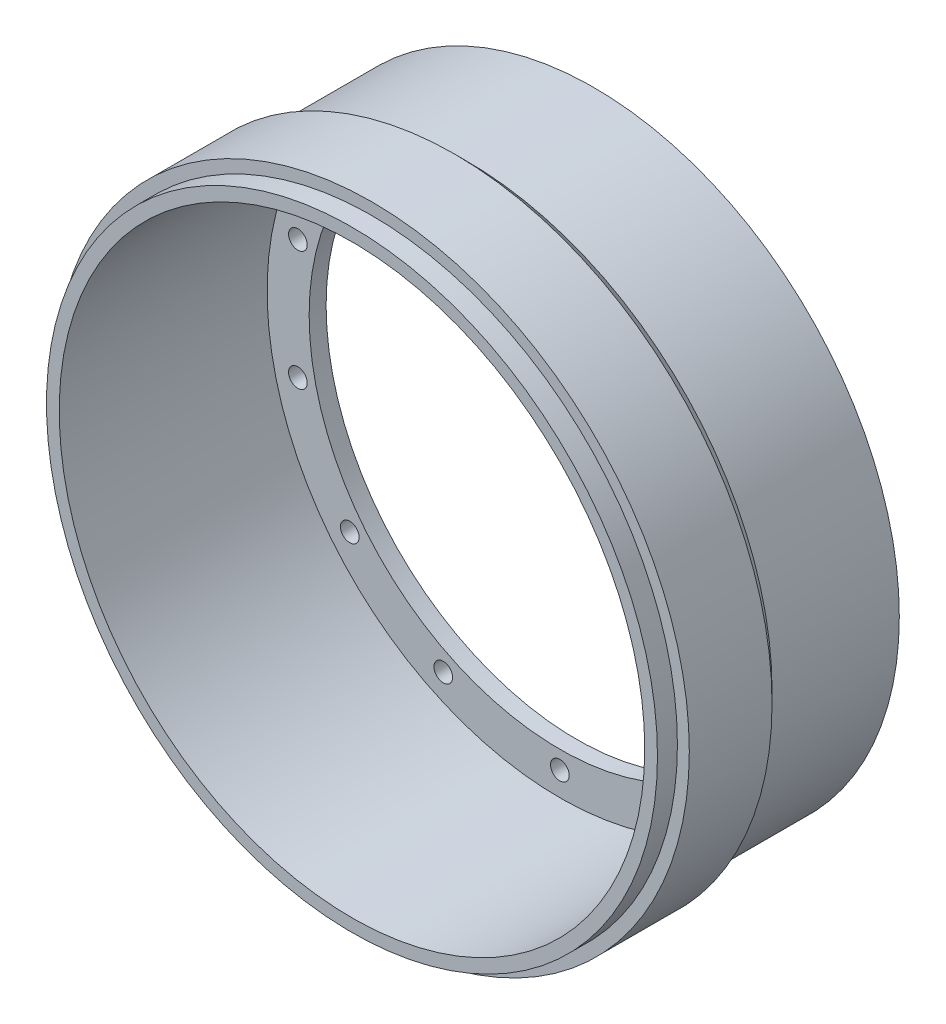
SolidWorks part; units mm, degrees
ref_plane "Front" through (0, 0, 0) normal (0, 0, 1) x (1, 0, 0)
ref_plane "Top" through (0, 0, 0) normal (0, 1, 0) x (1, 0, 0)
ref_plane "Right" through (0, 0, 0) normal (1, 0, 0) x (0, 0, -1)
sketch "Esquisse1" plane through (0, 0, 0) normal (1, 0, 0) x (0, 0, -1)
  line L0 (-14.8359, 0) -> (4.6594, 0) construction
  line L1 (0, 34.5) -> (0, 36)
  line L2 (0, 36) -> (-15, 36)
  line L3 (-16.4, 37.4) -> (-26.15, 37.4)
  line L4 (-26.15, 37.4) -> (-26.15, 36)
  line L5 (-26.15, 36) -> (-28.5, 36)
  line L6 (-28.5, 36) -> (-28.5, 34.5)
  line L7 (-28.5, 34.5) -> (-4, 34.5)
  line L8 (-4, 34.5) -> (-4, 29.55)
  line L9 (-4, 29.55) -> (-2, 29.55)
  line L10 (-2, 29.55) -> (-2, 34.5)
  line L11 (-2, 34.5) -> (0, 34.5)
  line L12 (0, 41.7159) -> (0, -1.6631) construction
  line L13 (-15, 36) -> (-16.4, 37.4)
  dimension "D1" = 59.1
  dimension "D2" = 69
  dimension "D3" = 74.8
  dimension "D4" = 72
  dimension "D5" = 72
  dimension "D7" = 2
  dimension "D8" = 2.35
  dimension "D9" = 9.75
  dimension "D6" = 45
  dimension "D10" = 15
revolve "Révolution1" add sketch "Esquisse1" angle 360 about L0
sketch "Esquisse2" plane through (0, 0, 4) normal (0, 0, 1) x (1, 0, 0)
  circle A1 centre (0, 31.67) radius 1.1
  circle A2 centre (0, 31.67) radius 1.1 construction
  circle A3 centre (13.7411, 28.5337) radius 1.1
  circle A4 centre (24.7606, 19.7459) radius 1.1
  circle A5 centre (30.876, 7.0472) radius 1.1
  circle A6 centre (30.876, -7.0472) radius 1.1
  circle A7 centre (24.7606, -19.7459) radius 1.1
  circle A8 centre (13.7411, -28.5337) radius 1.1
  circle A9 centre (0, -31.67) radius 1.1
  circle A10 centre (-13.7411, -28.5337) radius 1.1
  circle A11 centre (-24.7606, -19.7459) radius 1.1
  circle A12 centre (-30.876, -7.0472) radius 1.1
  circle A13 centre (-30.876, 7.0472) radius 1.1
  circle A14 centre (-24.7606, 19.7459) radius 1.1
  circle A15 centre (-13.7411, 28.5337) radius 1.1
  point P34 (0, 0)
  dimension "D1" = 14
extrude "Enlèv. mat.-Extru.1" cut sketch "Esquisse2" against normal through all
equation "\"D5@Esquisse1\"=\"D4@Esquisse1\""
